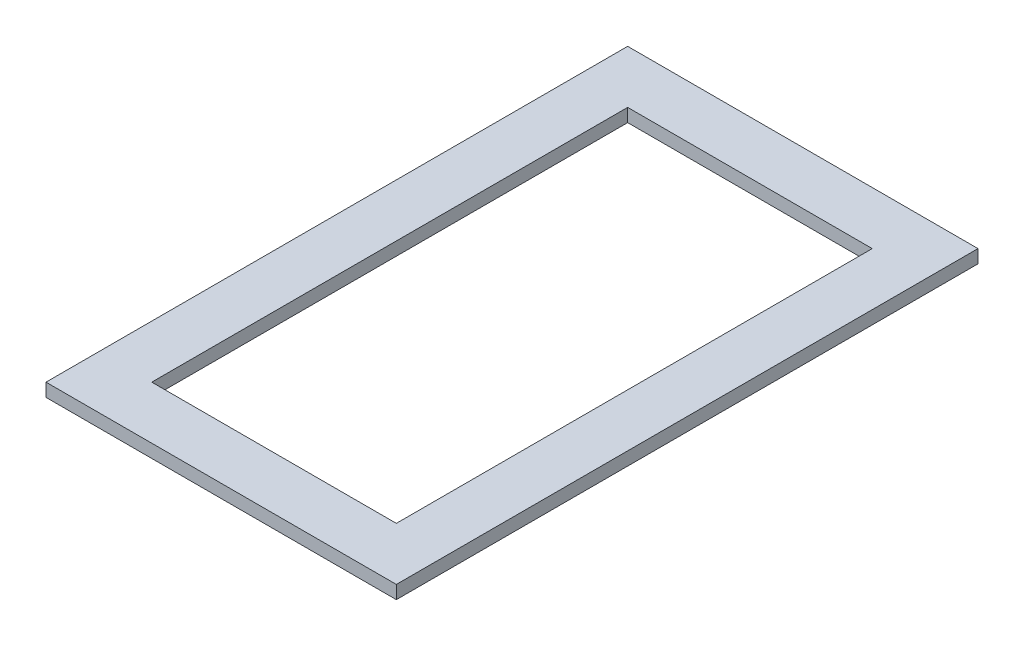
SolidWorks part; units mm, degrees
material "Щебень 40-20"
ref_plane "Спереди" through (0, 0, 0) normal (0, 0, 1) x (1, 0, 0)
ref_plane "Сверху" through (0, 0, 0) normal (0, 1, 0) x (1, 0, 0)
ref_plane "Справа" through (0, 0, 0) normal (1, 0, 0) x (0, 0, -1)
sketch "Эскиз1" plane through (0, 0, 0) normal (0, 1, 0) x (1, 0, 0)
  line L0 (3112.5, 5300) -> (-3112.5, 5300) construction
  line L1 (-3312.5, 5500) -> (3312.5, 5500)
  line L2 (-3312.5, 5500) -> (-3312.5, -5500)
  line L3 (-3312.5, -5500) -> (3312.5, -5500)
  line L4 (3312.5, 5500) -> (3312.5, -5500)
  line L5 (-2312.5, 4500) -> (2312.5, 4500)
  line L6 (-2312.5, 4500) -> (-2312.5, -4500)
  line L7 (-2312.5, -4500) -> (2312.5, -4500)
  line L8 (2312.5, 4500) -> (2312.5, -4500)
  line L9 (2512.5, 4700) -> (-2512.5, 4700) construction
  line L10 (-3112.5, 5300) -> (-3112.5, -5300) construction
  line L11 (-2512.5, 4700) -> (-2512.5, -4700) construction
  line L12 (3112.5, -5300) -> (3112.5, 5300) construction
  line L13 (2512.5, -4700) -> (2512.5, 4700) construction
  line L14 (-3112.5, -5300) -> (-2000, -5300) construction
  line L15 (-2000, -4700) -> (2000, -4700) construction
  dimension "D1" = 200
  dimension "D2" = 200
  dimension "D3" = 200
  dimension "D4" = 200
  dimension "D5" = 200
  dimension "D6" = 200
  dimension "D7" = 200
  dimension "D8" = 200
extrude "Бобышка-Вытянуть1" add sketch "Эскиз1" against normal blind 250
